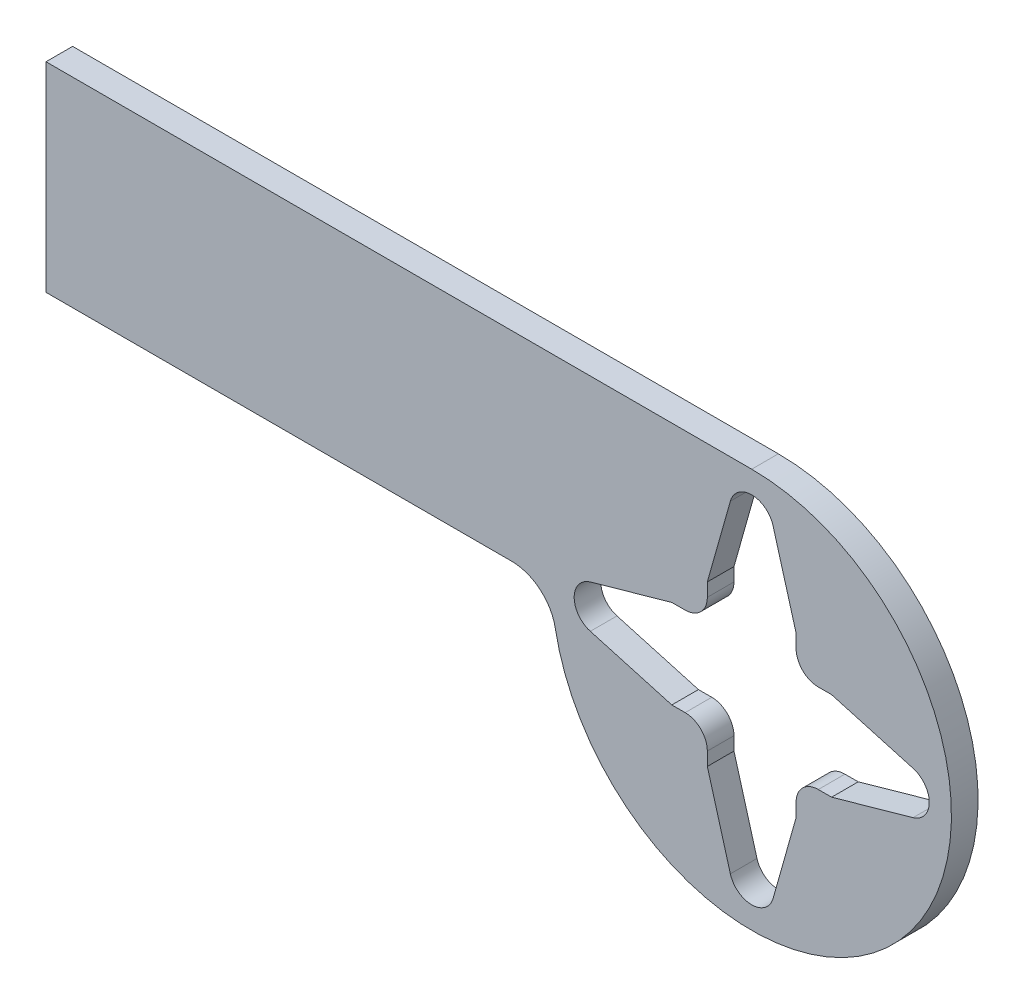
SolidWorks part; units mm, degrees
ref_plane "Front Plane" through (0, 0, 0) normal (0, 0, 1) x (1, 0, 0)
ref_plane "Top Plane" through (0, 0, 0) normal (0, 1, 0) x (1, 0, 0)
ref_plane "Right Plane" through (0, 0, 0) normal (1, 0, 0) x (0, 0, -1)
sketch "Sketch1" plane through (0, 0, 0) normal (0, 0, 1) x (1, 0, 0)
  line L0 (-5, 5) -> (-5, 9)
  line L8 (5, -5) -> (-5, -5)
  line L9 (5, -5) -> (5, 5)
  line L10 (5, 5) -> (-5, 5)
  line L11 (-5, -5) -> (-5, 5)
  line L12 (5, -5) -> (-5, 5) construction
  line L13 (5, 5) -> (-5, -5) construction
  line L14 (-5, 9) -> (-2.4058, 18.1799)
  line L15 (0, -55) -> (0, 55) construction
  line L16 (9, 5) -> (18.1799, 2.4058)
  line L17 (5, 5) -> (5, 9)
  line L18 (55, 0) -> (-55, 0) construction
  line L19 (5, -5) -> (5, -9)
  line L20 (-5, -9) -> (-2.4058, -18.1799)
  line L21 (5, -9) -> (2.4058, -18.1799)
  line L22 (-5, -5) -> (-5, -9)
  line L23 (5, -5) -> (9, -5)
  line L24 (9, -5) -> (18.1799, -2.4058)
  line L25 (-9, -5) -> (-18.1799, -2.4058)
  line L26 (5, 5) -> (9, 5)
  line L27 (-5, -5) -> (-9, -5)
  line L28 (-9, 5) -> (-18.1799, 2.4058)
  line L29 (5, 9) -> (2.4058, 18.1799)
  line L30 (-5, 5) -> (-9, 5)
  line L31 (0, 22.5) -> (-22.5, 0)
  line L32 (-22.5, 0) -> (-22.5, 22.5)
  line L33 (-22.5, 22.5) -> (0, 22.5)
  line L34 (-27.0416, 0) -> (-22.5, 0)
  line L35 (-22.5, 22.5) -> (-79.5, 22.5)
  line L36 (-22.5, 22.5) -> (-22.5, 0)
  line L37 (-22.5, 0) -> (-79.5, 0)
  line L38 (-79.5, 22.5) -> (-79.5, 0)
  line L41 (-22.5, 0) -> (-22.125, -4.0909)
  circle A0 centre (0, 0) radius 22.5
  circle A1 centre (0, 17.5) radius 2.5
  circle A2 centre (0, -17.5) radius 2.5
  circle A3 centre (17.5, 0) radius 2.5
  circle A4 centre (-17.5, 0) radius 2.5
  circle A5 centre (-7.5, 7.5) radius 2.5
  circle A6 centre (-7.5, -7.5) radius 2.5
  circle A7 centre (7.5, 7.5) radius 2.5
  circle A8 centre (7.5, -7.5) radius 2.5
  arc A9 (-27.0416, 0) -> (-22.125, -4.0909) centre (-27.0416, -5) cw
  dimension "D1" = 45
  dimension "D3" = 5
  dimension "D5" = 12.5
  dimension "D6" = 5
  dimension "D9" = 5
  dimension "D11" = 5
  dimension "D2" = 10
  dimension "D4" = 4
  dimension "D7" = 4
  dimension "D8" = 12.5
  dimension "D10" = 57
extrude "Boss-Extrude1" add sketch "Sketch1" along normal blind 3
